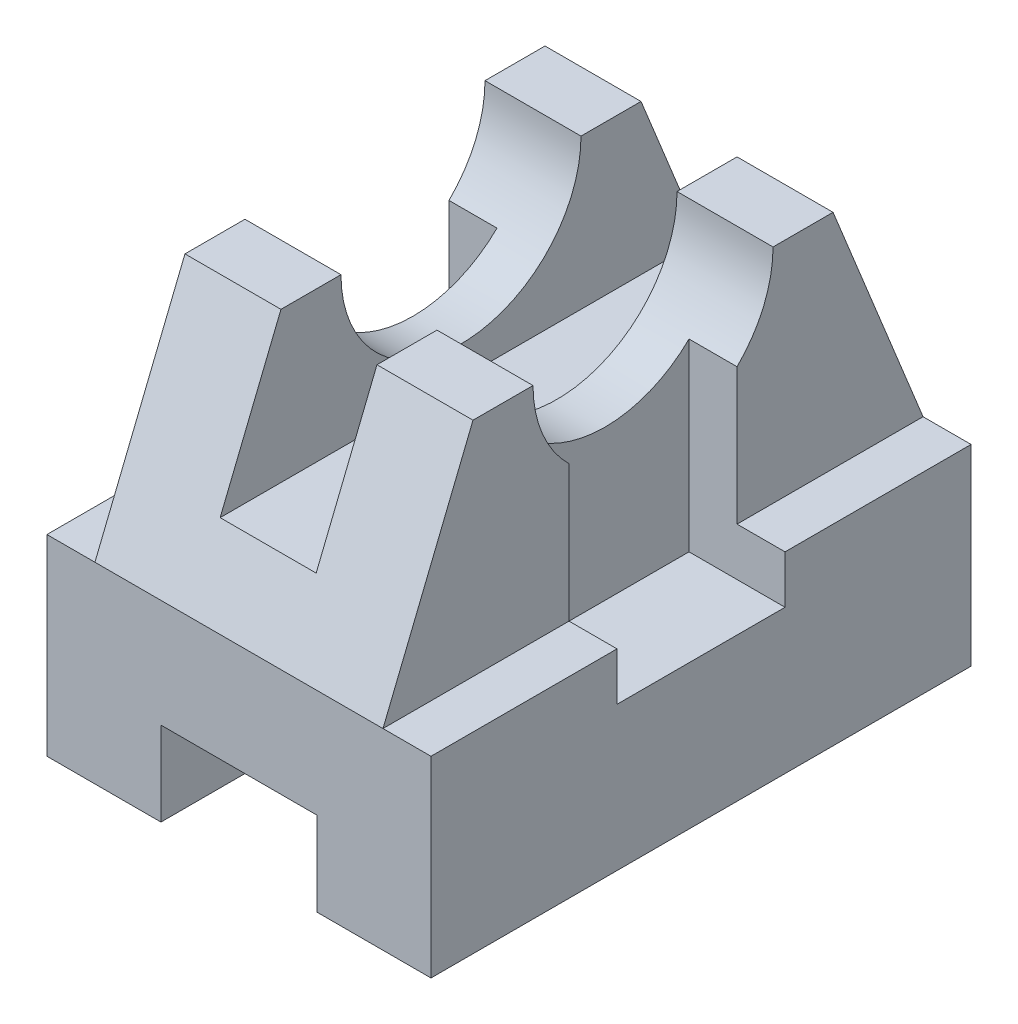
SolidWorks part; units mm, degrees
material "Plain Carbon Steel"
ref_plane "Front Plane" through (0, 0, 0) normal (0, 0, 1) x (1, 0, 0)
ref_plane "Top Plane" through (0, 0, 0) normal (0, 1, 0) x (1, 0, 0)
ref_plane "Right Plane" through (0, 0, 0) normal (1, 0, 0) x (0, 0, -1)
sketch "Sketch1" plane through (0, 0, 0) normal (0, 0, 1) x (1, 0, 0)
  line L0 (0, 0) -> (0, 32) construction
  line L1 (-32, 0) -> (-13, 0)
  line L2 (-13, 0) -> (-13, 14)
  line L3 (-13, 14) -> (13, 14)
  line L4 (13, 14) -> (13, 0)
  line L5 (13, 0) -> (32, 0)
  line L6 (32, 0) -> (32, 32)
  line L7 (32, 32) -> (-32, 32)
  line L8 (-32, 32) -> (-32, 0)
  dimension "D1" = 64
  dimension "D2" = 32
  dimension "D3" = 26
  dimension "D4" = 14
extrude "Boss-Extrude1" add sketch "Sketch1" along normal mid plane 90
sketch "Sketch2" plane through (0, 0, 0) normal (1, 0, 0) x (0, 0, -1)
  line L0 (0, 32) -> (0, 69) construction
  line L1 (-45, 32) -> (45, 32) construction
  line L2 (-45, 32) -> (45, 32)
  line L3 (45, 32) -> (30, 69)
  line L4 (30, 69) -> (-30, 69)
  line L5 (-30, 69) -> (-45, 32)
  dimension "D1" = 32
  dimension "D2" = 37
  dimension "D3" = 90
  dimension "D4" = 60
extrude "Boss-Extrude2" add sketch "Sketch2" along normal mid plane 48
sketch "Sketch3" plane through (0, 0, 0) normal (0, 0, 1) x (1, 0, 0)
  line L0 (0, 0) -> (0, 69) construction
  line L1 (24, 69) -> (-24, 69) construction
  line L2 (-8, 44) -> (8, 44)
  line L3 (8, 44) -> (8, 69)
  line L4 (8, 69) -> (-8, 69)
  line L5 (-8, 69) -> (-8, 44)
  dimension "D1" = 16
  dimension "D2" = 25
  dimension "D3" = 69
extrude "Cut-Extrude1" cut sketch "Sketch3" against normal through all and the other way through all
sketch "Sketch4" plane through (24, 0, 0) normal (1, 0, 0) x (0, 0, -1)
  line L0 (0, 32) -> (0, 69) construction
  line L1 (-45, 32) -> (45, 32) construction
  line L2 (30, 69) -> (-30, 69) construction
  circle A0 centre (0, 69) radius 20
  dimension "D1" = 40
extrude "Cut-Extrude2" cut sketch "Sketch4" against normal through all
sketch "Sketch5" plane through (0, 0, 0) normal (0, 0, 1) x (1, 0, 0)
  line L0 (0, 0) -> (0, 69) construction
  line L1 (-32, 24) -> (-16, 24)
  line L2 (-32, 32) -> (-32, 0) construction
  line L3 (-16, 24) -> (-16, 69)
  line L4 (-8, 69) -> (-24, 69) construction
  line L5 (-16, 69) -> (-32, 69)
  line L6 (-32, 69) -> (-32, 24)
  line L7 (16, 24) -> (32, 24)
  line L8 (32, 0) -> (32, 32) construction
  line L9 (32, 24) -> (32, 69)
  line L10 (32, 69) -> (16, 69)
  line L11 (24, 69) -> (8, 69) construction
  line L12 (16, 69) -> (16, 24)
  dimension "D1" = 64
  dimension "D2" = 16
  dimension "D3" = 24
  dimension "D4" = 45
extrude "Cut-Extrude3" cut sketch "Sketch5" against normal mid plane 28
